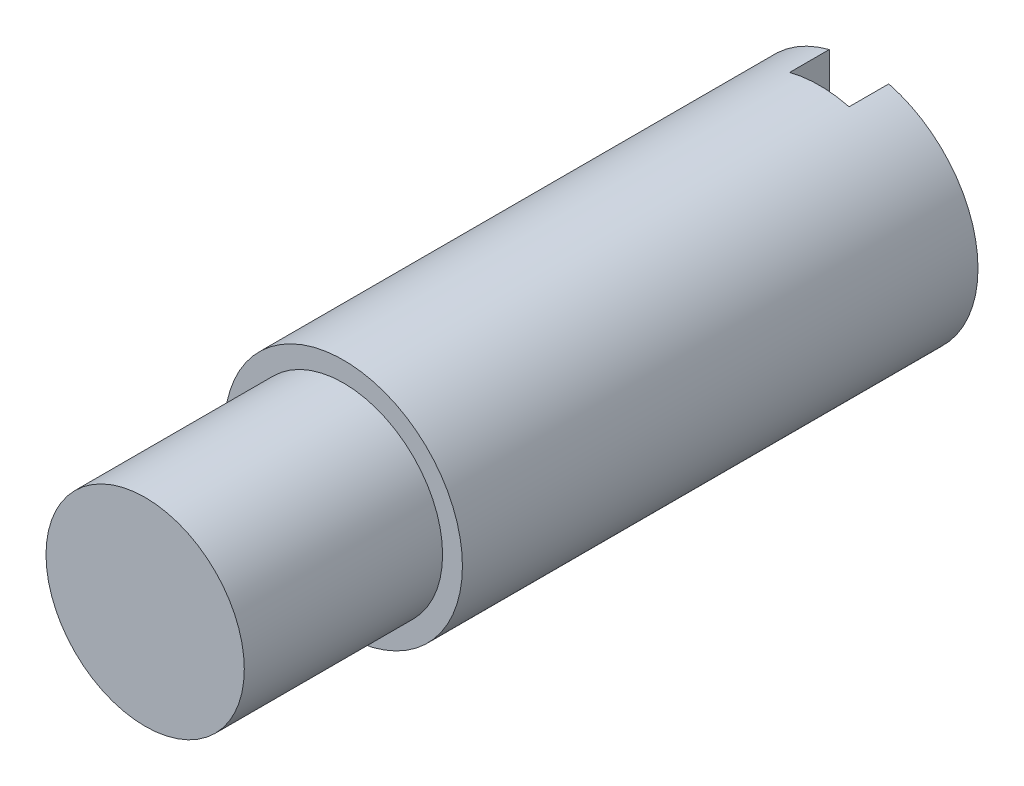
SolidWorks part; units mm, degrees
ref_plane "Спереди" through (0, 0, 0) normal (0, 0, 1) x (1, 0, 0)
ref_plane "Сверху" through (0, 0, 0) normal (0, 1, 0) x (1, 0, 0)
ref_plane "Справа" through (0, 0, 0) normal (1, 0, 0) x (0, 0, -1)
sketch "Эскиз1" plane through (0, 0, 0) normal (0, 0, 1) x (1, 0, 0)
  circle A0 centre (0, 0) radius 3
  dimension "D1" = 6
extrude "Бобышка-Вытянуть1" add sketch "Эскиз1" along normal blind 13
sketch "Эскиз2" plane through (0, 0, 13) normal (0, 0, 1) x (1, 0, 0)
  circle A0 centre (0, 0) radius 2.5
  dimension "D1" = 5
extrude "Бобышка-Вытянуть2" add sketch "Эскиз2" along normal blind 5
sketch "Эскиз3" plane through (0, 0, 0) normal (0, 0, -1) x (-1, 0, 0)
  line L1 (-0.75, 3.6129) -> (0.75, 3.6129)
  line L2 (-0.75, 3.6129) -> (-0.75, -3.5139)
  line L3 (-0.75, -3.5139) -> (0.75, -3.5139)
  line L4 (0.75, 3.6129) -> (0.75, -3.5139)
  point P4 (0, 3.6129)
  dimension "D1" = 0
  dimension "D2" = 1.5
extrude "Вырез-Вытянуть1" cut sketch "Эскиз3" against normal blind 1
